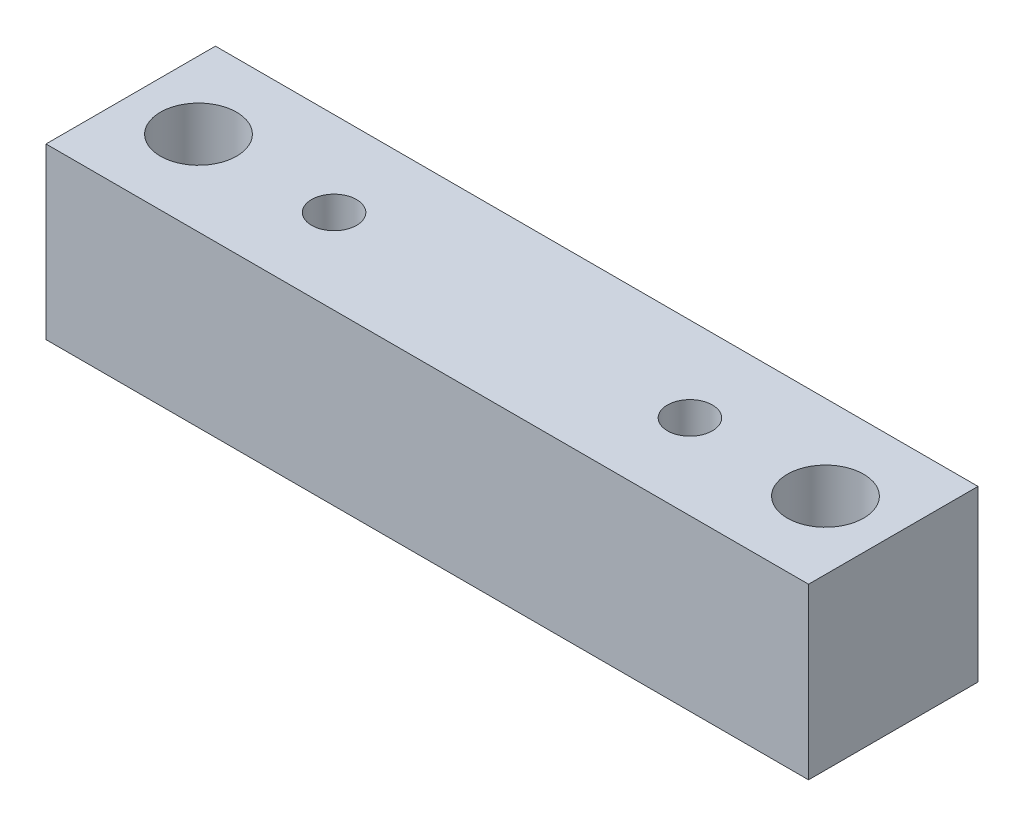
SolidWorks part; units mm, degrees
ref_plane "Front Plane" through (0, 0, 0) normal (0, 0, 1) x (1, 0, 0)
ref_plane "Top Plane" through (0, 0, 0) normal (0, 1, 0) x (1, 0, 0)
ref_plane "Right Plane" through (0, 0, 0) normal (1, 0, 0) x (0, 0, -1)
sketch "Sketch1" plane through (0, 0, 0) normal (0, 1, 0) x (1, 0, 0)
  line L0 (-21, 0) -> (21, 0) construction
  line L1 (-45, -10) -> (45, -10)
  line L2 (-45, -10) -> (-45, 10)
  line L3 (-45, 10) -> (45, 10)
  line L4 (45, -10) -> (45, 10)
  line L5 (-45, -10) -> (45, 10) construction
  line L6 (-45, 10) -> (45, -10) construction
  line L7 (-45, 0) -> (-37, 0) construction
  line L8 (45, 0) -> (37, 0) construction
  circle A0 centre (-21, 0) radius 2.65
  circle A1 centre (21, 0) radius 2.65
  circle A2 centre (-37, 0) radius 2.75
  circle A3 centre (37, 0) radius 2.75
  point P0 (0, 0)
  point P9 (0, 0)
  dimension "D4" = 8
  dimension "D1" = 42
  dimension "D2" = 90
  dimension "D3" = 20
  dimension "D5" = 8
extrude "Boss-Extrude1" add sketch "Sketch1" along normal blind 20
sketch "Sketch2" plane through (0, 0, 0) normal (0, -1, 0) x (1, 0, 0)
  line L1 (-16.2657, 0) -> (-18.6329, 4.1)
  line L2 (-18.6329, 4.1) -> (-23.3671, 4.1)
  line L3 (-23.3671, 4.1) -> (-25.7343, 0)
  line L4 (-25.7343, 0) -> (-23.3671, -4.1)
  line L5 (-23.3671, -4.1) -> (-18.6329, -4.1)
  line L6 (-18.6329, -4.1) -> (-16.2657, 0)
  line L7 (25.7343, 0) -> (23.3671, 4.1)
  line L8 (23.3671, 4.1) -> (18.6329, 4.1)
  line L9 (18.6329, 4.1) -> (16.2657, 0)
  line L10 (16.2657, 0) -> (18.6329, -4.1)
  line L11 (18.6329, -4.1) -> (23.3671, -4.1)
  line L12 (23.3671, -4.1) -> (25.7343, 0)
  circle A0 centre (-21, 0) radius 4.1 construction
  circle A1 centre (21, 0) radius 4.1 construction
  dimension "D1" = 8.2
  dimension "D2" = 8.2
extrude "Cut-Extrude1" cut sketch "Sketch2" against normal blind 14
sketch "Sketch3" plane through (0, 20, 0) normal (0, 1, 0) x (1, 0, 0)
  circle A0 centre (-37, 0) radius 4.5
  circle A1 centre (37, 0) radius 4.5
extrude "Cut-Extrude2" cut sketch "Sketch3" against normal blind 13
